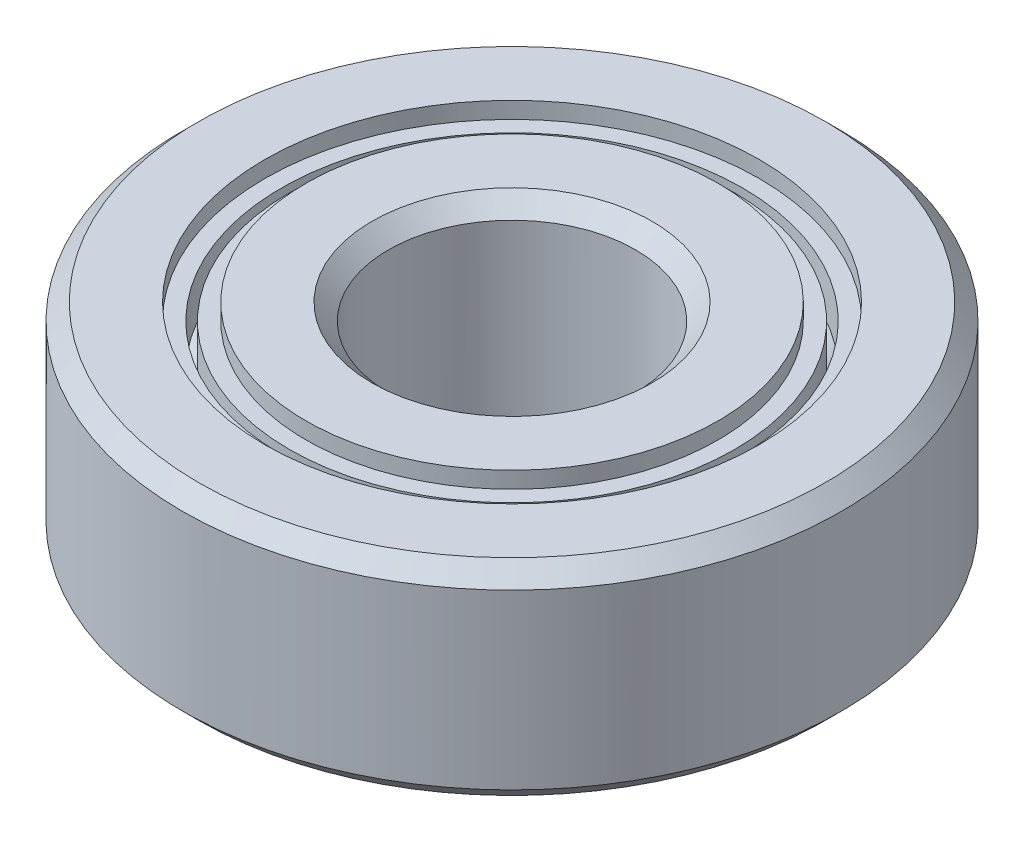
SolidWorks part; units mm, degrees
ref_plane "Front Plane" through (0, 0, 0) normal (0, 0, 1) x (1, 0, 0)
ref_plane "Top Plane" through (0, 0, 0) normal (0, 1, 0) x (1, 0, 0)
ref_plane "Right Plane" through (0, 0, 0) normal (1, 0, 0) x (0, 0, -1)
sketch "Sketch1" plane through (0, 0, 0) normal (1, 0, 0) x (0, 0, -1)
  line L0 (1.5, -0.25) -> (1.5, 25) construction
  line L1 (1.5, -0.25) -> (2.5, -0.25)
  line L2 (4, -0.25) -> (4, 2.25)
  line L3 (4, 2.25) -> (3, 2.25)
  line L4 (1.5, 2.25) -> (1.5, -0.25)
  line L5 (0, 0) -> (0, 1.9269) construction
  line L6 (2.75, 1.525) -> (2.75, 2) construction
  line L7 (2.8, -0.0495) -> (2.8, 0.4774)
  line L8 (2.7, -0.0495) -> (2.7, 0.4774)
  line L9 (2.7, 1.525) -> (2.7, 2) construction
  line L10 (2.8, 1.525) -> (2.8, 2) construction
  line L11 (2.8, 1.5226) -> (2.8, 2.0495)
  line L12 (2.7, 1.5226) -> (2.7, 2.0495)
  line L13 (3, -0.25) -> (4, -0.25)
  line L14 (2.75, 1) -> (4.5892, 1) construction
  line L15 (2.8, 2.0495) -> (3, 2.0495)
  line L16 (2.5, 2.25) -> (2.5, 2.0495)
  line L17 (2.5, 2.0495) -> (2.7, 2.0495)
  line L18 (3, 2.25) -> (3, 2.0495)
  line L19 (2.5, 2.25) -> (1.5, 2.25)
  line L20 (3, -0.25) -> (3, -0.0495)
  line L21 (2.8, -0.0495) -> (3, -0.0495)
  line L22 (2.5, -0.25) -> (2.5, -0.0495)
  line L23 (2.5, -0.0495) -> (2.7, -0.0495)
  arc A0 (2.7, 1.5226) -> (2.7, 0.4774) centre (2.75, 1) ccw
  arc A1 (2.8, 0.4774) -> (2.8, 1.5226) centre (2.75, 1) ccw
  point P11 (1.5, 1)
  point P12 (2.75, 2)
  dimension "D1" = 4
  dimension "D2" = 2.5
  dimension "D3" = 1.5
  dimension "D7" = 0.5
  dimension "D9" = 0.2005
  dimension "D10" = 0.25
  dimension "D5" = 0.05
  dimension "D6" = 0.05
revolve "Revolve1" add sketch "Sketch1" angle 360 about L5
sketch "Sketch2" plane through (0, 0, 0) normal (0, 0, 1) x (1, 0, 0)
  line L0 (2.75, -0.2356) -> (2.75, 2.3718) construction
  line L1 (4, 2.25) -> (-4, 2.25) construction
  line L2 (2.75, 1.5) -> (2.75, 0.5)
  arc A0 (2.75, 0.5) -> (2.75, 1.5) centre (2.75, 1) ccw
  dimension "D2" = 1
  dimension "D1" = 2.75
  dimension "D3" = 1.25
revolve "Revolve2" add sketch "Sketch2" angle 360 about L0
pattern_circular "CirPattern2" count 17 over 360 about axis through (0, 0, 0) along (0, 1, 0) of bodies 103
chamfer "Chamfer1" distance 0.2 distance2 0.2 2 edges at (0, -0.25, -4) (0, 2.25, -4)
chamfer "Chamfer2" distance 0.2 angle 45 2 edges at (0, 2.25, -1.5) (0, -0.25, -1.5)
